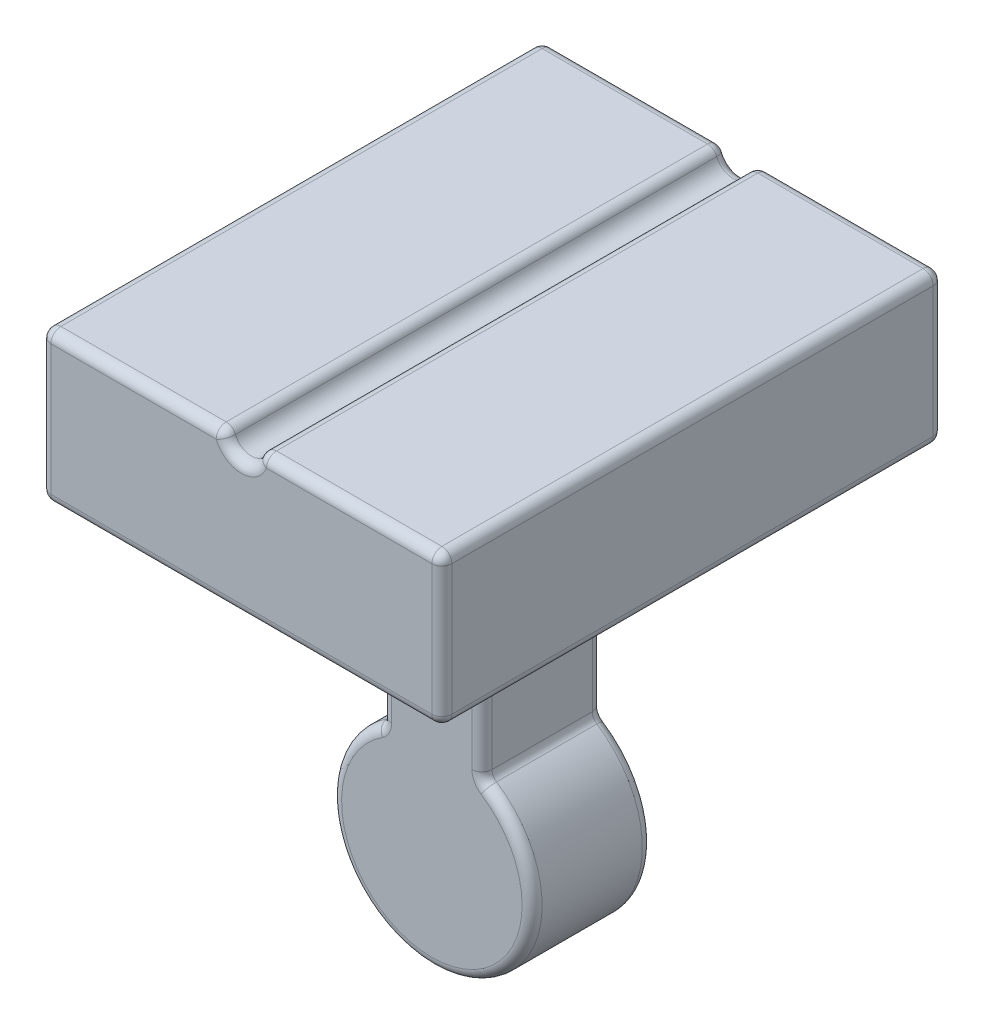
SolidWorks part; units mm, degrees
ref_plane "前视基准面" through (0, 0, 0) normal (0, 0, 1) x (1, 0, 0)
ref_plane "上视基准面" through (0, 0, 0) normal (0, 1, 0) x (1, 0, 0)
ref_plane "右视基准面" through (0, 0, 0) normal (1, 0, 0) x (0, 0, -1)
sketch "草图1" plane through (0, 0, 0) normal (0, 0, 1) x (1, 0, 0)
  line L0 (-5, 10) -> (-5, 30)
  line L1 (0, 0) -> (5, 0)
  line L4 (5, 0) -> (5, 10)
  line L5 (0, 0) -> (-5, 0)
  line L8 (-5, 0) -> (-5, 10)
  line L9 (-5, 30) -> (5, 30)
  line L10 (5, 30) -> (5, 10)
  arc A0 (-5, 8.6603) -> (5, 8.6603) centre (0, 0) ccw
  dimension "D1" = 20
  dimension "D2" = 30
  dimension "D3" = 5
  dimension "D5" = 5
extrude "凸台-拉伸1" add sketch "草图1" along normal blind 12 contours L10 L9 L0 L8 L5 L1 L4 | L8 A0 L4 L1 L5
sketch "草图2" plane through (0, 30, 0) normal (0, 1, 0) x (1, 0, 0)
  line L1 (-20, 19) -> (20, 19)
  line L2 (-20, 19) -> (-20, -31)
  line L3 (-20, -31) -> (20, -31)
  line L4 (20, 19) -> (20, -31)
  line L5 (-20, 19) -> (20, -31) construction
  line L6 (-20, -31) -> (20, 19) construction
  point P0 (0, -6)
  dimension "D1" = 50
  dimension "D2" = 40
extrude "凸台-拉伸2" add sketch "草图2" along normal blind 15
sketch "草图3" plane through (0, 0, -19) normal (0, 0, -1) x (-1, 0, 0)
  line L0 (-20, 45) -> (20, 45) construction
  circle A0 centre (0, 45) radius 1.7
  dimension "D1" = 3.4
extrude "切除-拉伸2" cut sketch "草图3" against normal blind 53
fillet "圆角1" radius 1 30 edges at (0, 30, 12) (0, 30, 0) (0, -10, 12) (0, -10, 0) (20, 30, 6) (5, 8.6603, 6) (5, 19.3301, 12) (5, 30, 6) (5, 19.3301, 0) (-5, 30, 6) (-5, 19.3301, 12) (-5, 8.6603, 6) (-5, 19.3301, 0) (20, 37.5, 31) (0, 30, 31) (0, 43.3, 31) (-20, 37.5, 31) (-20, 30, 6) (-10.85, 45, 31) (-20, 45, 6) (1.7, 45, 6) (-1.7, 45, 6) (20, 45, 6) (10.85, 45, 31) (-20, 37.5, -19) (0, 30, -19) (20, 37.5, -19) (10.85, 45, -19) (0, 43.3, -19) (-10.85, 45, -19)
